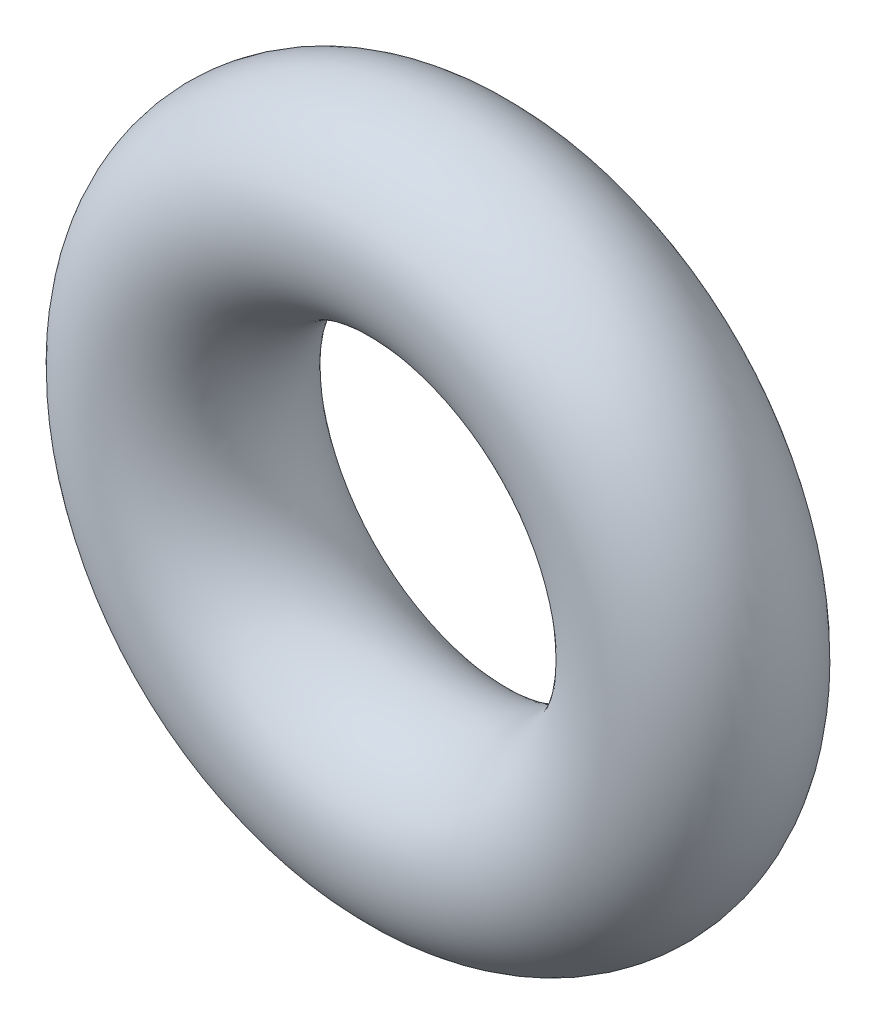
SolidWorks part; units mm, degrees
material "Резина"
ref_plane "Спереди" through (0, 0, 0) normal (0, 0, 1) x (1, 0, 0)
ref_plane "Сверху" through (0, 0, 0) normal (0, 1, 0) x (1, 0, 0)
ref_plane "Справа" through (0, 0, 0) normal (1, 0, 0) x (0, 0, -1)
sketch "Эскиз1" plane through (0, 0, 0) normal (0, 1, 0) x (1, 0, 0)
  line L0 (0, 0) -> (0, 4.9277) construction
  circle A0 centre (2.5, 0) radius 0.95
  dimension "D1" = 1.9
  dimension "D2" = 2.5
revolve "Повернуть1" add sketch "Эскиз1" angle 360 about L0
